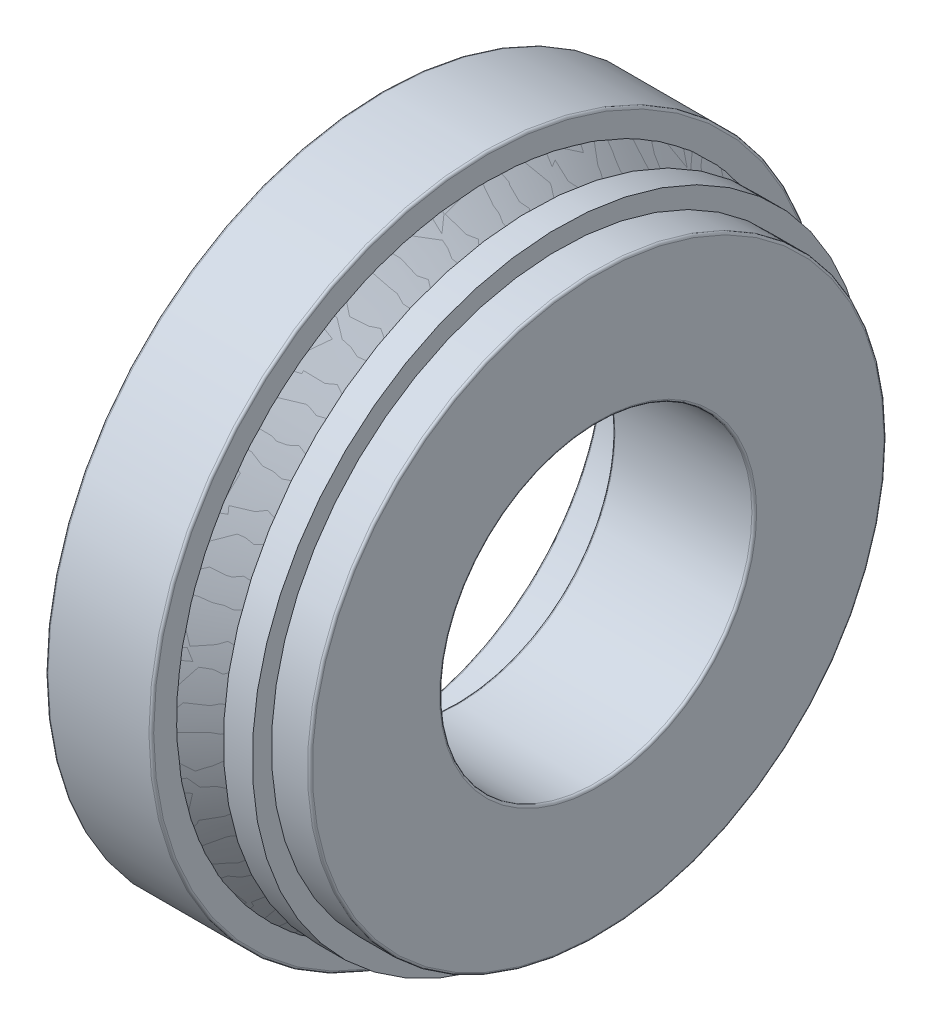
SolidWorks part; units mm, degrees
material "SKF_Blau"
ref_plane "Vorne" through (0, 0, 0) normal (0, 0, 1) x (1, 0, 0)
ref_plane "Oben" through (0, 0, 0) normal (0, 1, 0) x (1, 0, 0)
ref_plane "Rechts" through (0, 0, 0) normal (1, 0, 0) x (0, 0, -1)
sketch "Skizze1" plane through (0, 0, 0) normal (0, 0, 1) x (1, 0, 0)
  line L0 (0, 0) -> (-43.7726, 0) construction
  line L1 (0, 32.5) -> (0, 0) construction
  line L2 (-29.5, 32.5) -> (0, 32.5)
  line L3 (-45, 45.75) -> (-45, 70)
  line L4 (-45, 70) -> (-23, 70)
  line L5 (0, 32.5) -> (0, 60)
  line L6 (42, 0) -> (-71.7683, 88.8855) construction
  line L7 (-45, 45.75) -> (-36, 45.75)
  line L8 (-23, 64.74) -> (-23, 70)
  line L9 (-8, 60) -> (-8, 64)
  line L10 (-29.5, 32.5) -> (-29.5, 39.25)
  line L11 (-39.3355, 49.087) -> (-26.163, 35.9145)
  line L12 (-32.7493, 42.5007) -> (-16.7557, 58.4943) construction
  line L13 (-8.2057, 49.9443) -> (-25.3057, 67.0443)
  line L14 (0, 60) -> (-8, 60)
  line L15 (-8, 64) -> (-14, 64)
  line L16 (-14, 64) -> (-14, 55.74)
  line L17 (-23, 64.74) -> (-14, 55.74)
  line L18 (-36, 45.75) -> (-29.5, 39.25)
  arc A0 (-25.3057, 67.0443) -> (-39.3355, 49.087) centre (42, 0) ccw
  arc A1 (-8.2057, 49.9443) -> (-26.163, 35.9145) centre (-75.25, 117.25) cw
  point P26 (-32.75, 42.5)
  dimension "D4" = 95
  dimension "D1" = 65
  dimension "D2" = 140
  dimension "D3" = 45
  dimension "D5" = 42
  dimension "D6" = 29.5
  dimension "D7" = 91.5
  dimension "D8" = 22
  dimension "D9" = 45
  dimension "D10" = 120
  dimension "D11" = 6
  dimension "D12" = 4
  dimension "D13" = 8
  dimension "D14" = 0.001
  dimension "D15" = 0.001
  dimension "D16" = 9
  dimension "D17" = 38
revolve "Rotation1" add sketch "Skizze1" angle 360 about L0
fillet "Verrundung1" radius 0.5 6 edges at (-45, 0, -45.75) (-29.5, 0, -32.5) (0, 0, -32.5) (0, 0, -60) (-23, 0, -70) (-45, 0, -70)
